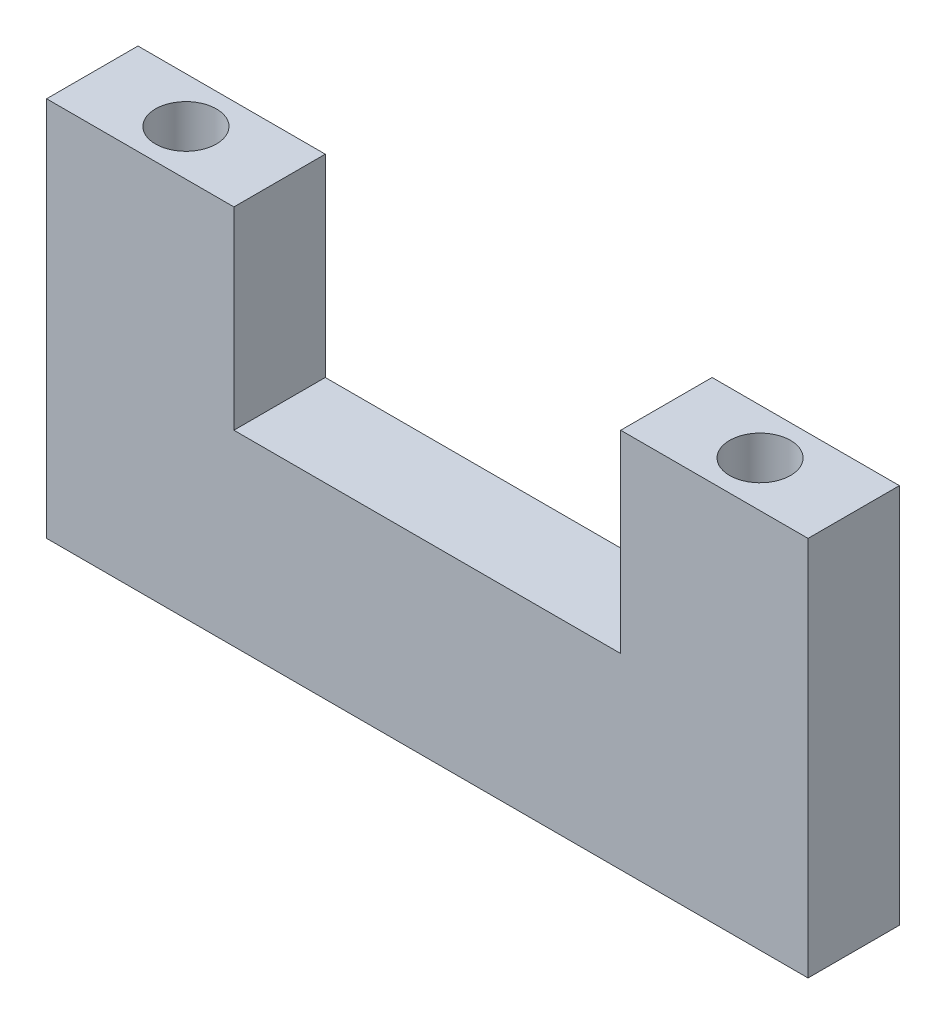
SolidWorks part; units mm, degrees
ref_plane "Front Plane" through (0, 0, 0) normal (0, 0, 1) x (1, 0, 0)
ref_plane "Top Plane" through (0, 0, 0) normal (0, 1, 0) x (1, 0, 0)
ref_plane "Right Plane" through (0, 0, 0) normal (1, 0, 0) x (0, 0, -1)
sketch "Sketch1" plane through (0, 0, 0) normal (0, 0, 1) x (1, 0, 0)
  line L1 (-12.5, 6.25) -> (12.5, 6.25)
  line L2 (-12.5, 6.25) -> (-12.5, -6.25)
  line L3 (-12.5, -6.25) -> (12.5, -6.25)
  line L4 (12.5, 6.25) -> (12.5, -6.25)
  line L5 (-12.5, 6.25) -> (12.5, -6.25) construction
  line L6 (-12.5, -6.25) -> (12.5, 6.25) construction
  point P0 (0, 0)
  dimension "D1" = 25
  dimension "D2" = 12.5
extrude "Boss-Extrude1" add sketch "Sketch1" along normal blind 3
sketch "Sketch2" plane through (0, 0, 3) normal (0, 0, 1) x (1, 0, 0)
  line L0 (12.5, 6.25) -> (-12.5, 6.25) construction
  line L1 (-6.35, 6.25) -> (6.35, 6.25)
  line L2 (-6.35, 6.25) -> (-6.35, -0.1)
  line L3 (-6.35, -0.1) -> (6.35, -0.1)
  line L4 (6.35, 6.25) -> (6.35, -0.1)
  line L5 (-12.5, -6.25) -> (12.5, -6.25) construction
  dimension "D1" = 6.15
  dimension "D2" = 6.15
  dimension "D3" = 6.15
extrude "Cut-Extrude1" cut sketch "Sketch2" against normal blind 3
sketch "Sketch3" plane through (0, 6.25, 0) normal (0, 1, 0) x (1, 0, 0)
  line L0 (-6.35, 0) -> (-12.5, 0) construction
  line L1 (12.5, 0) -> (6.35, 0) construction
  line L2 (-12.5, -3) -> (-12.5, 0) construction
  line L3 (12.5, -3) -> (12.5, 0) construction
  circle A0 centre (-9.425, -1.5) radius 1
  circle A1 centre (9.425, -1.5) radius 1
  point P12 (0, 0)
  dimension "D1" = 2
  dimension "D3" = 2
  dimension "D2" = 1.5
  dimension "D4" = 1.5
  dimension "D5" = 3.075
  dimension "D6" = 3.075
extrude "Cut-Extrude2" cut sketch "Sketch3" against normal blind 5 contours A0
sketch "Sketch4" plane through (0, 6.25, 0) normal (0, 1, 0) x (1, 0, 0)
  line L0 (12.5, -3) -> (12.5, 0) construction
  line L1 (12.5, -3) -> (6.35, -3) construction
  circle A0 centre (9.425, -1.5) radius 1
  dimension "D1" = 2
  dimension "D2" = 3.075
  dimension "D3" = 1.5
extrude "Cut-Extrude3" cut sketch "Sketch4" against normal blind 5
